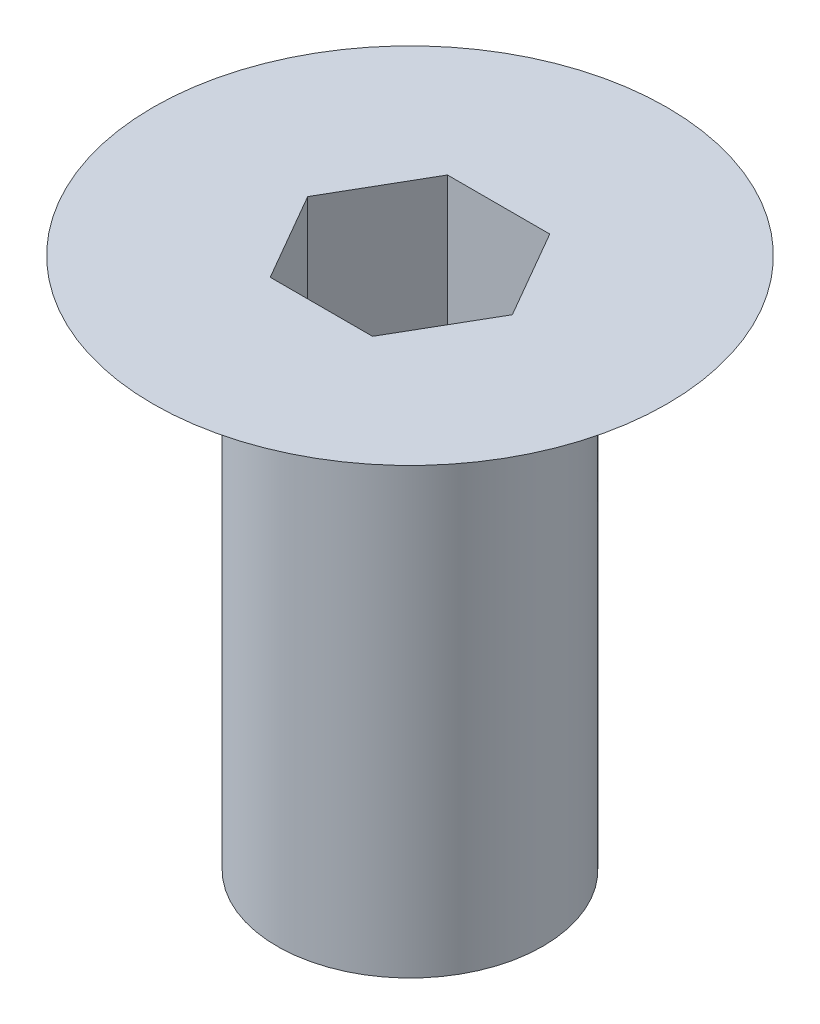
SolidWorks part; units mm, degrees
material "1023 Carbon Steel Sheet (SS)"
ref_plane "Front Plane" through (0, 0, 0) normal (0, 0, 1) x (1, 0, 0)
ref_plane "Top Plane" through (0, 0, 0) normal (0, 1, 0) x (1, 0, 0)
ref_plane "Right Plane" through (0, 0, 0) normal (1, 0, 0) x (0, 0, -1)
sketch "Sketch1" plane through (0, 0, 0) normal (0, 0, 1) x (1, 0, 0)
  line L0 (0, 0) -> (-2.9, 0)
  line L1 (-2.9, 0) -> (-1.5, -0.8412)
  line L2 (-1.5, -0.8412) -> (-1.5, -6)
  line L3 (-1.5, -6) -> (0, -6)
  line L4 (0, -6) -> (0, 0) construction
  line L5 (0, 0) -> (0, -6)
  dimension "D1" = 6
  dimension "D2" = 59
  dimension "D3" = 5.8
  dimension "D4" = 3
revolve "Revolve1" add sketch "Sketch1" angle 360 about L4
sketch "Sketch2" plane through (0, 0, 0) normal (0, 1, 0) x (1, 0, 0)
  line L1 (0.5774, 1) -> (-0.5774, 1)
  line L2 (-0.5774, 1) -> (-1.1547, 0)
  line L3 (-1.1547, 0) -> (-0.5774, -1)
  line L4 (-0.5774, -1) -> (0.5774, -1)
  line L5 (0.5774, -1) -> (1.1547, 0)
  line L6 (1.1547, 0) -> (0.5774, 1)
  circle A0 centre (0, 0) radius 1 construction
  dimension "D1" = 2
extrude "Cut-Extrude1" cut sketch "Sketch2" against normal blind 1.5
